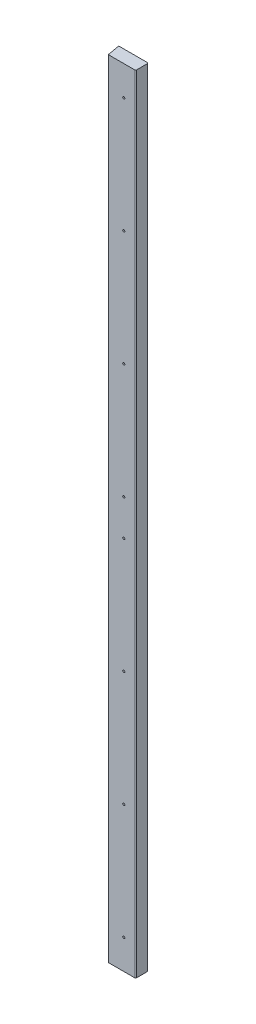
SolidWorks part; units mm, degrees
ref_plane "Front" through (0, 0, 0) normal (0, 0, 1) x (1, 0, 0)
ref_plane "Top" through (0, 0, 0) normal (0, 1, 0) x (1, 0, 0)
ref_plane "Right" through (0, 0, 0) normal (1, 0, 0) x (0, 0, -1)
sketch "Sketch1" plane through (0, 0, 0) normal (0, 1, 0) x (1, 0, 0)
  line L0 (-44.45, 19.05) -> (-37.7319, -19.05)
  line L1 (44.45, 19.05) -> (-44.45, 19.05)
  line L2 (44.45, 19.05) -> (44.45, -19.05)
  line L3 (44.45, -19.05) -> (-37.7319, -19.05)
  line L4 (-44.45, 19.05) -> (-44.45, -19.05) construction
  line L5 (44.45, 19.05) -> (-44.45, -19.05) construction
  line L6 (44.45, -19.05) -> (-44.45, 19.05) construction
  line L7 (-37.7319, -19.05) -> (-44.45, -19.05) construction
  point P0 (0, 0)
  dimension "D1" = 38.1
  dimension "D2" = 88.9
  dimension "D3" = 80
extrude "Boss-Extrude1" add sketch "Sketch1" along normal blind 2362.2
ref_plane "Plane1" through (0, 1181.1, 0) normal (0, -1, 0) x (-1, 0, 0)
hole_wizard "1/4 (0.25) Diameter Hole1" positions "Sketch2" profile "Sketch3" hole size "1/4" standard "ANSI Inch" end condition through all
sketch "Sketch2" plane through (0, 0, 19.05) normal (0, 0, -1) x (-1, 0, 0)
  line L2 (37.7319, 2362.2) -> (37.7319, 0) construction
  line L3 (-20.955, 1181.1) -> (20.955, 1181.1) construction
  point P0 (-8.8174, 88.9)
  point P33 (-8.8174, 434.975)
  point P34 (-8.8174, 781.05)
  point P35 (-8.8174, 1127.125)
  point P44 (0, 0)
  point P45 (0, 0)
  dimension "D1" = 53.975
  dimension "D3" = 46.5494
  dimension "D4" = 346.075
  dimension "D2" = 4
sketch "Sketch3" plane through (8.8174, 88.9, 19.05) normal (1, 0, 0) x (0, -1, 0)
  line L0 (0, 0) -> (0, 38.1)
  line L1 (0, 38.1) -> (3.175, 38.1)
  line L2 (3.175, 38.1) -> (3.175, 0)
  line L5 (3.175, 0) -> (0, 0)
  line L11 (0, -6.35) -> (0, 107.95) construction
  dimension "Thru Hole Dia." = 6.35
  dimension "Thru Hole Depth" = 38.1
fillet "Fillet2" radius 3.175 2 edges at (44.45, 1181.1, 19.05) (44.45, 1181.1, -19.05)
mirror "Mirror1" about plane through (0, 1181.1, 0) normal (0, -1, 0) of "1/4 (0.25) Diameter Hole1"
